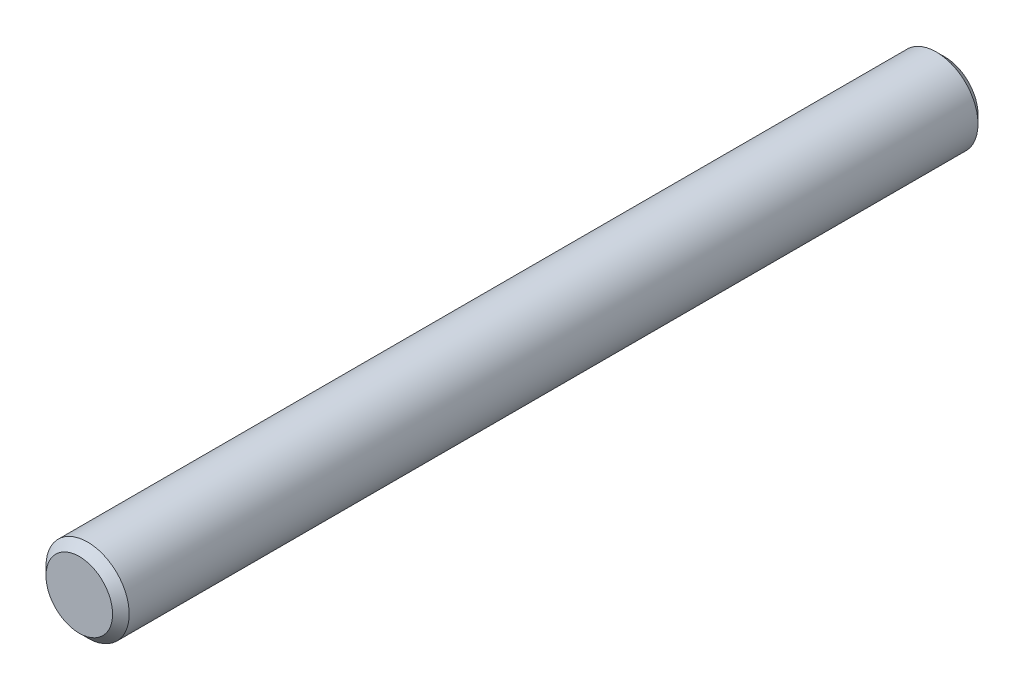
SolidWorks part; units mm, degrees
ref_plane "Front Plane" through (0, 0, 0) normal (0, 0, 1) x (1, 0, 0)
ref_plane "Top Plane" through (0, 0, 0) normal (0, 1, 0) x (1, 0, 0)
ref_plane "Right Plane" through (0, 0, 0) normal (1, 0, 0) x (0, 0, -1)
sketch "Sketch1" plane through (0, 0, 0) normal (0, 0, 1) x (1, 0, 0)
  circle A0 centre (0, 0) radius 2.5
  dimension "D1" = 5
extrude "Boss-Extrude1" add sketch "Sketch1" along normal blind 52
chamfer "Chamfer1" distance 0.5 angle 45 2 edges at (2.5, 0, 52) (2.5, 0, 0)
